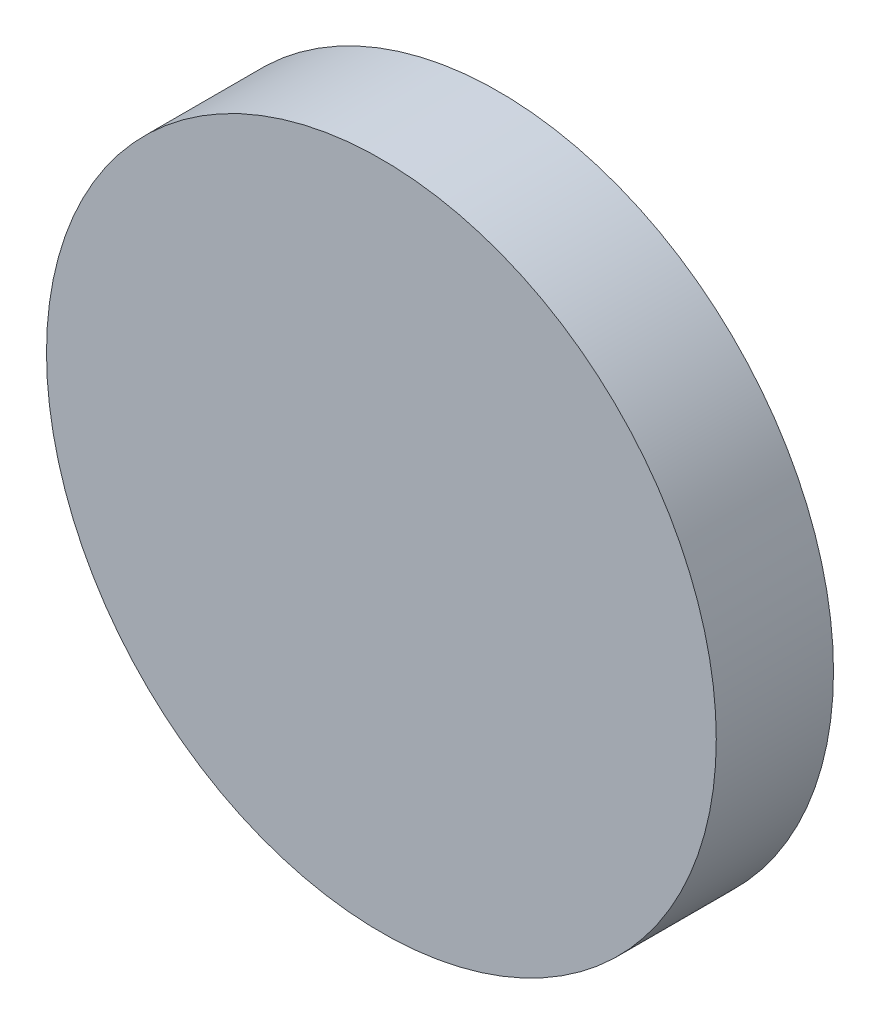
SolidWorks part; units mm, degrees
ref_plane "前视基准面" through (0, 0, 0) normal (0, 0, 1) x (1, 0, 0)
ref_plane "上视基准面" through (0, 0, 0) normal (0, 1, 0) x (1, 0, 0)
ref_plane "右视基准面" through (0, 0, 0) normal (1, 0, 0) x (0, 0, -1)
sketch "草图1" plane through (0, 0, 0) normal (0, 0, 1) x (1, 0, 0)
  circle A0 centre (0, 0) radius 10
  dimension "D1" = 20
extrude "凸台-拉伸1" add sketch "草图1" along normal blind 3.5
